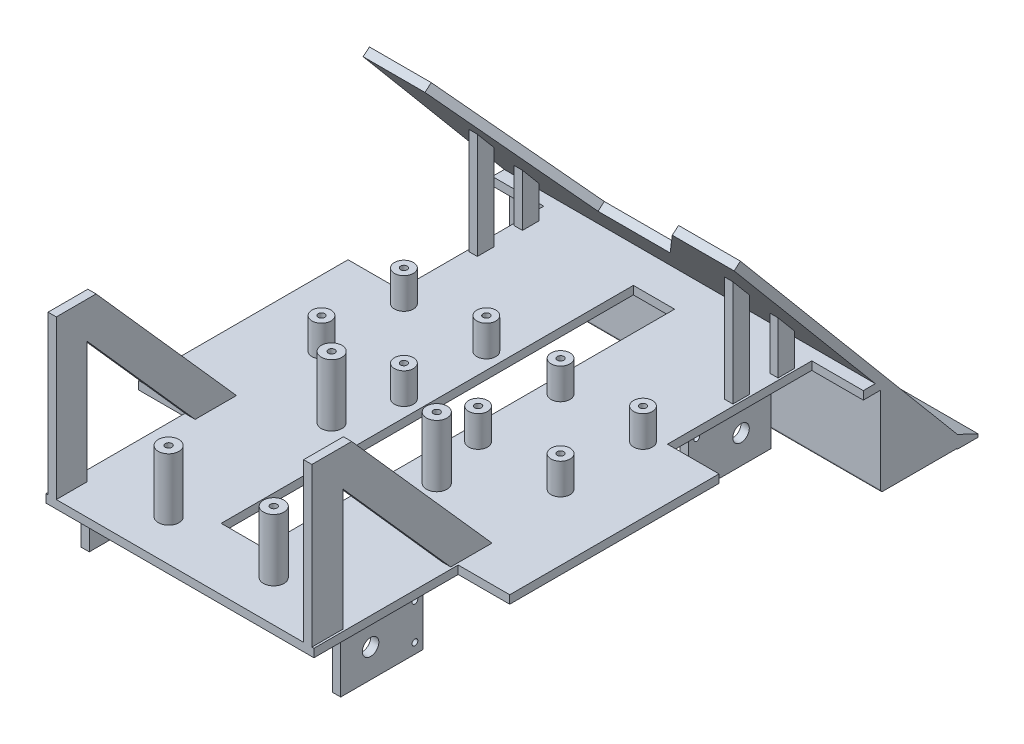
SolidWorks part; units mm, degrees
ref_plane "Front Plane" through (0, 0, 0) normal (0, 0, 1) x (1, 0, 0)
ref_plane "Top Plane" through (0, 0, 0) normal (0, 1, 0) x (1, 0, 0)
ref_plane "Right Plane" through (0, 0, 0) normal (1, 0, 0) x (0, 0, -1)
sketch "Sketch1" plane through (0, 0, 0) normal (0, 1, 0) x (1, 0, 0)
  line L1 (0, 0) -> (180, 0)
  line L2 (0, 0) -> (0, 250)
  line L3 (0, 250) -> (180, 250)
  line L4 (180, 0) -> (180, 250)
  line L5 (0, 0) -> (180, 250) construction
  line L6 (0, 250) -> (180, 0) construction
  point P4 (90, 125)
  dimension "D1" = 250
  dimension "D2" = 180
extrude "Boss-Extrude1" add sketch "Sketch1" along normal blind 4
ref_plane "Plane2" through (0, 124.7537, -148.6756) normal (0, 0.6428, -0.766) x (-1, 0, 0)
sketch "Sketch3" plane through (0, 124.7537, -148.6756) normal (0, 0.6428, -0.766) x (-1, 0, 0)
  line L0 (-180, 3.0642) -> (-180, -157.6327) construction
  line L1 (-180, -153.6185) -> (0, -153.6185)
  line L2 (-180, -153.6185) -> (-180, -160.6969)
  line L3 (-180, -160.6969) -> (0, -160.6969)
  line L4 (0, -153.6185) -> (0, -160.6969)
  line L5 (-180, -153.6185) -> (0, -160.6969) construction
  line L6 (-180, -160.6969) -> (0, -153.6185) construction
  point P4 (-90, -157.1577)
extrude "Cut-Extrude1" cut sketch "Sketch3" against normal blind 2
sketch "Sketch4" plane through (0, 123.4681, -147.1435) normal (0, 0.6428, -0.766) x (-1, 0, 0)
  line L0 (-180, 3.0642) -> (-180, -155.9545) construction
  line L1 (-180, -49.3572) -> (0, -49.3572)
  line L2 (-180, -49.3572) -> (-180, -217.9168)
  line L3 (-180, -217.9168) -> (0, -217.9168)
  line L4 (0, -49.3572) -> (0, -217.9168)
  line L5 (-180, -49.3572) -> (0, -217.9168) construction
  line L6 (-180, -217.9168) -> (0, -49.3572) construction
  point P4 (-90, -133.637)
extrude "Boss-Extrude3" add sketch "Sketch4" along normal blind 4
sketch "Sketch5" plane through (0, 0, 0) normal (-1, 0, 0) x (0, 0, 1)
  line L0 (-287.2178, -43.4659) -> (-287.2178, -37.243)
  line L1 (-290.2819, -40.8947) -> (-181.9339, 88.2294) construction
  line L2 (-287.2178, -37.243) -> (-290.2819, -40.8947)
  line L3 (-290.2819, -40.8947) -> (-287.2178, -43.4659)
extrude "Cut-Extrude2" cut sketch "Sketch5" against normal blind 214
sketch "Sketch6" plane through (0, 0, 0) normal (0, -1, 0) x (1, 0, 0)
  line L0 (0, -183.7456) -> (180, -183.7456) construction
  line L1 (0, -250) -> (0, 0) construction
  line L2 (180, 0) -> (180, -250) construction
  line L3 (0, -250.7456) -> (180, -250.7456) construction
  line L4 (0, -15) -> (180, -15) construction
  line L5 (27, -183.7456) -> (31, -183.7456)
  line L6 (27, -183.7456) -> (27, -223.7456)
  line L7 (27, -223.7456) -> (31, -223.7456)
  line L8 (31, -183.7456) -> (31, -223.7456)
  line L9 (27, -183.7456) -> (31, -223.7456) construction
  line L10 (27, -223.7456) -> (31, -183.7456) construction
  line L11 (0, 0) -> (180, 0) construction
  line L12 (90, -15) -> (90, -183.7456) construction
  line L13 (27, -15) -> (31, -15)
  line L14 (27, -15) -> (27, -55)
  line L15 (27, -55) -> (31, -55)
  line L16 (31, -15) -> (31, -55)
  line L17 (27, -15) -> (31, -55) construction
  line L18 (27, -55) -> (31, -15) construction
  line L19 (153, -223.7456) -> (149, -223.7456)
  line L20 (149, -183.7456) -> (149, -223.7456)
  line L21 (153, -183.7456) -> (149, -183.7456)
  line L22 (153, -183.7456) -> (153, -223.7456)
  line L23 (153, -55) -> (149, -55)
  line L24 (149, -15) -> (149, -55)
  line L25 (153, -15) -> (149, -15)
  line L26 (153, -15) -> (153, -55)
  point P12 (29, -203.7456)
  point P21 (29, -35)
  dimension "D1" = 67
  dimension "D2" = 4
  dimension "D3" = 27
  dimension "D4" = 40
  dimension "D5" = 15
  dimension "D6" = 4
  dimension "D7" = 40
  dimension "D8" = 27
extrude "Boss-Extrude4" add sketch "Sketch6" along normal blind 25
sketch "Sketch7" plane through (0, 126.0392, -150.2077) normal (0, 0.6428, -0.766) x (-1, 0, 0)
  line L0 (-90, -49.3572) -> (-90, -213.1498) construction
  line L1 (0, -49.3572) -> (-180, -49.3572) construction
  line L2 (-180, -213.1498) -> (0, -213.1498) construction
  line L3 (-180, -217.9168) -> (0, -217.9168) construction
  line L4 (-130, -167.9168) -> (-50, -167.9168)
  line L5 (-130, -167.9168) -> (-130, -217.9168)
  line L6 (-130, -217.9168) -> (-50, -217.9168)
  line L7 (-50, -167.9168) -> (-50, -217.9168)
  line L8 (-130, -167.9168) -> (-50, -217.9168) construction
  line L9 (-130, -217.9168) -> (-50, -167.9168) construction
  line L10 (-150, -49.3572) -> (-107.5, -113.8755)
  line L11 (-107.5, -113.8755) -> (-72.5, -113.8755)
  line L12 (-72.5, -113.8755) -> (-30, -49.3572)
  line L13 (-30, -49.3572) -> (-150, -49.3572)
  line L14 (-180, 3.0642) -> (-180, -155.9545) construction
  point P10 (-90, -192.9168)
  point P13 (-90, -167.9168)
  point P20 (-90, -113.8755)
  dimension "D1" = 80
  dimension "D2" = 50
  dimension "D3" = 30
  dimension "D4" = 35
extrude "Cut-Extrude3" cut sketch "Sketch7" against normal blind 5
sketch "Sketch8" plane through (27, 0, 0) normal (-1, 0, 0) x (0, 0, 1)
  line L0 (-187.7456, 0) -> (-187.7456, -25) construction
  line L1 (-183.7456, 0) -> (-223.7456, 0) construction
  line L2 (-183.7456, -25) -> (-223.7456, -25) construction
  line L3 (-183.7456, -25) -> (-183.7456, 0) construction
  line L4 (-51, 0) -> (-51, -25) construction
  line L5 (-15, 0) -> (-55, 0) construction
  line L6 (-15, -25) -> (-55, -25) construction
  line L7 (-55, -25) -> (-55, 0) construction
  circle A0 centre (-187.7456, -2.5) radius 1.4
  circle A1 centre (-187.7456, -20) radius 1.4
  circle A2 centre (-51, -2.5) radius 1.4
  circle A3 centre (-51, -20) radius 1.4
  dimension "D1" = 2.8
  dimension "D5" = 2.8
  dimension "D2" = 17.5
  dimension "D3" = 2.5
  dimension "D4" = 4
  dimension "D6" = 2.5
  dimension "D7" = 17.5
  dimension "D8" = 4
extrude "Cut-Extrude4" cut sketch "Sketch8" against normal blind 155
sketch "Sketch10" plane through (0, 0, -287.2178) normal (0, 0, -1) x (-1, 0, 0)
  line L1 (-180, -37.243) -> (-130, -37.243)
  line L2 (-180, -37.243) -> (-180, -43.4659)
  line L3 (-180, -43.4659) -> (-130, -43.4659)
  line L4 (-130, -37.243) -> (-130, -43.4659)
  line L5 (-180, -37.243) -> (-130, -43.4659) construction
  line L6 (-180, -43.4659) -> (-130, -37.243) construction
  line L7 (-50, -37.243) -> (0, -37.243)
  line L8 (-50, -37.243) -> (-50, -43.4659)
  line L9 (-50, -43.4659) -> (0, -43.4659)
  line L10 (0, -37.243) -> (0, -43.4659)
  line L11 (-50, -37.243) -> (0, -43.4659) construction
  line L12 (-50, -43.4659) -> (0, -37.243) construction
  point P4 (-155, -40.3544)
  point P11 (-25, -40.3544)
extrude "Boss-Extrude5" add sketch "Sketch10" along normal blind 10
sketch "Sketch11" plane through (0, 0, 0) normal (-1, 0, 0) x (0, 0, 1)
  line L0 (-297.2178, -41.9659) -> (-287.2178, -37.243)
  line L1 (-297.2178, -43.4659) -> (-297.2178, -37.243) construction
  line L2 (-297.2178, -37.243) -> (-287.2178, -37.243) construction
  line L3 (-297.2178, -43.4659) -> (-287.2178, -43.4659) construction
  line L4 (-297.2178, -41.9659) -> (-297.2178, -37.243)
  line L5 (-297.2178, -37.243) -> (-287.2178, -37.243)
  dimension "D1" = 1.5
extrude "Cut-Extrude5" cut sketch "Sketch11" against normal blind 199
sketch "Sketch12" plane through (0, 4, 0) normal (0, 1, 0) x (1, 0, 0)
  line L0 (90, 0) -> (90, 307.2534) construction
  line L1 (0, 0) -> (180, 0) construction
  line L3 (80, 230) -> (100, 230)
  line L4 (80, 230) -> (80, 30)
  line L5 (80, 30) -> (100, 30)
  line L6 (100, 230) -> (100, 30)
  line L7 (80, 230) -> (100, 30) construction
  line L8 (80, 30) -> (100, 230) construction
  point P8 (90, 130)
  point P9 (90, 230)
  dimension "D1" = 20
  dimension "D2" = 30
  dimension "D3" = 200
extrude "Cut-Extrude6" cut sketch "Sketch12" against normal blind 5
sketch "Sketch13" plane through (0, 4, 0) normal (0, 1, 0) x (1, 0, 0)
  line L0 (0, 0) -> (180, 0) construction
  line L1 (64.5, 99.1) -> (115.5, 99.1) construction
  line L2 (64.5, 99.1) -> (64.5, 20) construction
  line L3 (64.5, 20) -> (115.5, 20) construction
  line L4 (115.5, 99.1) -> (115.5, 20) construction
  circle A0 centre (115.5, 99.1) radius 1.6
  circle A1 centre (64.5, 99.1) radius 1.6
  circle A2 centre (64.5, 20) radius 1.6
  circle A3 centre (115.5, 20) radius 1.6
  circle A4 centre (64.5, 99.1) radius 5
  circle A5 centre (115.5, 99.1) radius 5
  circle A6 centre (115.5, 20) radius 5
  circle A7 centre (64.5, 20) radius 5
  point P4 (87.5576, 87.4411)
  point P7 (90, 0)
  point P8 (90, 20)
  dimension "D3" = 3.2
  dimension "D4" = 10
  dimension "D5" = 20
  dimension "D1" = 79.1
  dimension "D2" = 51
extrude "Boss-Extrude6" add sketch "Sketch13" along normal blind 30
sketch "Sketch14" plane through (0, 4, 0) normal (0, 1, 0) x (1, 0, 0)
  line L0 (0, 146.6712) -> (80, 146.6712) construction
  line L1 (32, 166.6712) -> (72, 166.6712) construction
  line L2 (32, 166.6712) -> (32, 126.6712) construction
  line L3 (32, 126.6712) -> (72, 126.6712) construction
  line L4 (72, 166.6712) -> (72, 126.6712) construction
  line L5 (32, 166.6712) -> (72, 126.6712) construction
  line L6 (32, 126.6712) -> (72, 166.6712) construction
  line L7 (108, 166.6712) -> (148, 166.6712) construction
  line L8 (108, 166.6712) -> (108, 126.6712) construction
  line L9 (108, 126.6712) -> (148, 126.6712) construction
  line L10 (148, 166.6712) -> (148, 126.6712) construction
  line L11 (108, 166.6712) -> (148, 126.6712) construction
  line L12 (108, 126.6712) -> (148, 166.6712) construction
  line L13 (0, 247.3892) -> (0, 0) construction
  line L14 (80, 230) -> (80, 30) construction
  line L15 (100, 146.6712) -> (180, 146.6712) construction
  line L16 (100, 30) -> (100, 230) construction
  line L17 (180, 0) -> (180, 247.3892) construction
  line L18 (50, 287.2178) -> (0, 287.2178) construction
  circle A0 centre (32, 166.6712) radius 1.6
  circle A1 centre (72, 166.6712) radius 1.6
  circle A2 centre (32, 126.6712) radius 1.6
  circle A3 centre (72, 126.6712) radius 1.6
  circle A4 centre (108, 166.6712) radius 1.6
  circle A5 centre (148, 166.6712) radius 1.6
  circle A6 centre (108, 126.6712) radius 1.6
  circle A7 centre (148, 126.6712) radius 1.6
  circle A8 centre (32, 166.6712) radius 4.6
  circle A9 centre (72, 166.6712) radius 4.6
  circle A10 centre (72, 126.6712) radius 4.6
  circle A11 centre (32, 126.6712) radius 4.6
  circle A12 centre (108, 166.6712) radius 4.6
  circle A13 centre (148, 166.6712) radius 4.6
  circle A14 centre (148, 126.6712) radius 4.6
  circle A15 centre (108, 126.6712) radius 4.6
  point P4 (40, 146.6712)
  point P9 (140, 146.6712)
  point P24 (40, 146.6712)
  point P26 (140, 146.6712)
  point P42 (128, 146.6712)
  point P43 (52, 146.6712)
  dimension "D2" = 3.2
  dimension "D4" = 3
  dimension "D1" = 40
  dimension "D3" = 120.5466
  dimension "D5" = 8
  dimension "D6" = 8
extrude "Boss-Extrude7" add sketch "Sketch14" along normal blind 15
ref_plane "Plane3" through (30, 0, 0) normal (-1, 0, 0) x (0, 0, 1)
sketch "Sketch15" plane through (30, 0, 0) normal (-1, 0, 0) x (0, 0, 1)
  line L0 (0, 4) -> (0, 80.7504)
  line L1 (-15, 4) -> (-15, 63)
  line L2 (-247.3892, 4) -> (0, 4) construction
  line L3 (-19.3019, 80.7504) -> (-87.4193, 4)
  line L4 (-15, 63) -> (-67.3636, 4)
  line L5 (-15, 4) -> (0, 4)
  line L6 (-87.4193, 4) -> (-67.3636, 4)
  line L7 (-19.3019, 80.7504) -> (0, 80.7504)
  dimension "D2" = 15
  dimension "D3" = 15
extrude "Boss-Extrude8" add sketch "Sketch15" along normal blind 4
ref_plane "Plane4" through (90, 0, 0) normal (1, 0, 0) x (0, 0, -1)
mirror "Mirror1" about plane through (90, 0, 0) normal (1, 0, 0) of "Boss-Extrude8"
sketch "Sketch16" plane through (30, 0, 0) normal (-1, 0, 0) x (0, 0, 1)
  line L0 (-212.2711, 45.8521) -> (-212.2711, 4)
  line L1 (-247.3892, 4) -> (-178.8698, 85.6583) construction
  line L2 (-247.3892, 4) -> (0, 4) construction
  line L3 (-212.2711, 4) -> (-204.2711, 4)
  line L4 (-204.2711, 4) -> (-204.2711, 55.3862)
  line L5 (-204.2711, 55.3862) -> (-212.2711, 45.8521)
  line L6 (-234.1848, 19.7364) -> (-234.1848, 4)
  line L7 (-234.1848, 4) -> (-226.1848, 4)
  line L8 (-226.1848, 4) -> (-226.1848, 29.2704)
  line L9 (-226.1848, 29.2704) -> (-234.1848, 19.7364)
  dimension "D1" = 8
  dimension "D2" = 8
extrude "Boss-Extrude9" add sketch "Sketch16" along normal blind 4
mirror "Mirror2" about plane through (90, 0, 0) normal (1, 0, 0) of "Boss-Extrude9"
sketch "Sketch17" plane through (0, 4, 0) normal (0, 1, 0) x (1, 0, 0)
  line L0 (0, 247.3892) -> (0, 0) construction
  line L1 (0, 70) -> (25, 70)
  line L2 (0, 70) -> (0, 0)
  line L3 (0, 0) -> (25, 0)
  line L4 (25, 70) -> (25, 0)
  line L5 (0, 70) -> (25, 0) construction
  line L6 (0, 0) -> (25, 70) construction
  line L7 (0, 0) -> (26, 0) construction
  line L8 (0, 287.2178) -> (0, 181.9339) construction
  line L9 (0, 241.5539) -> (25, 241.5539)
  line L10 (0, 241.5539) -> (0, 171.5539)
  line L11 (0, 171.5539) -> (25, 171.5539)
  line L12 (25, 241.5539) -> (25, 171.5539)
  line L13 (0, 241.5539) -> (25, 171.5539) construction
  line L14 (0, 171.5539) -> (25, 241.5539) construction
  point P4 (12.5, 35)
  point P13 (12.5, 206.5539)
  dimension "D1" = 25
  dimension "D2" = 70
  dimension "D3" = 25
  dimension "D4" = 70
extrude "Cut-Extrude8" cut sketch "Sketch17" against normal blind 19 contours L2 L3 L4 L1 | L10 L9 L12 L11
sketch "Sketch18" plane through (27, 0, 0) normal (-1, 0, 0) x (0, 0, 1)
  line L0 (-55, -12.5) -> (-15, -12.5) construction
  line L3 (-51, -2.5) -> (-51, -20) construction
  line L5 (-15, 0) -> (-55, 0) construction
  line L6 (-223.7456, -11.2) -> (-183.7456, -11.2) construction
  line L7 (-223.7456, -25) -> (-223.7456, 0) construction
  line L8 (-183.7456, -25) -> (-183.7456, 0) construction
  line L10 (-187.7456, -2.5) -> (-187.7456, -20) construction
  circle A0 centre (-29.5, -11.2) radius 4
  circle A2 centre (-209.2456, -11.2) radius 4
  dimension "D2" = 8
  dimension "D4" = 8
  dimension "D1" = 21.5
  dimension "D3" = 11.2
  dimension "D5" = 21.5
extrude "Cut-Extrude9" cut sketch "Sketch18" against normal blind 145
mirror "Mirror3" about plane through (90, 0, 0) normal (1, 0, 0) of "Cut-Extrude8"
sketch "Sketch19" plane through (0, 0, 0) normal (-1, 0, 0) x (0, 0, 1)
  line L0 (-250, 0.8886) -> (-250, -43.0527)
  line L1 (-250, -43.0527) -> (-287.7102, -43.0527)
  line L3 (-252.9065, -2.5753) -> (-252.9065, -40.0527)
  line L4 (-287.2178, -43.4659) -> (-250, 0.8886) construction
  line L5 (-252.9065, -40.0527) -> (-284.3538, -40.0527)
  line L6 (-284.3538, -40.0527) -> (-287.7102, -43.0527)
  line L7 (-252.9065, -2.5753) -> (-250, 0.8886)
  line L8 (-287.2178, -43.4659) -> (-250, 0.8886) construction
  line L9 (-250, 0.8886) -> (-250, 0) construction
  dimension "D1" = 2.9065
  dimension "D2" = 3
extrude "Boss-Extrude10" add sketch "Sketch19" against normal blind 180 separate body
sketch "Sketch23" plane through (50, 0, 0) normal (1, 0, 0) x (0, 0, -1)
  line L0 (250, 0.8886) -> (287.7102, -43.0527)
  line L1 (287.7102, -43.0527) -> (250, -43.0527)
  line L2 (250, -43.0527) -> (250, 0.8886)
sketch "Sketch27" plane through (0, 123.4681, -147.1435) normal (0, 0.6428, -0.766) x (-1, 0, 0)
  line L0 (-180, -164.5379) -> (0, -164.5379) construction
  line L1 (-130, -167.9168) -> (-50, -167.9168)
  line L2 (-130, -167.9168) -> (-130, -164.5379)
  line L3 (-130, -164.5379) -> (-50, -164.5379)
  line L4 (-50, -167.9168) -> (-50, -164.5379)
  line L5 (-130, -167.9168) -> (-50, -164.5379) construction
  line L6 (-130, -164.5379) -> (-50, -167.9168) construction
  line L7 (-50, -213.1498) -> (-50, -167.9168) construction
  point P4 (-90, -166.2274)
extrude "Boss-Extrude17" add sketch "Sketch27" along normal blind 3
extrude "Boss-Extrude13" add sketch "Sketch23" against normal blind 3
sketch "Sketch24" plane through (130, 0, 0) normal (-1, 0, 0) x (0, 0, 1)
  line L0 (-252.9065, -2.5753) -> (-252.9065, -40.0527)
  line L1 (-252.9065, -40.0527) -> (-284.3538, -40.0527)
  line L2 (-284.3538, -40.0527) -> (-252.9065, -2.5753)
extrude "Boss-Extrude14" add sketch "Sketch24" against normal blind 3
sketch "Sketch25" plane through (0, 0, 0) normal (-1, 0, 0) x (0, 0, 1)
  line L0 (-252.9065, -2.5753) -> (-252.9065, -40.0527)
  line L1 (-252.9065, -40.0527) -> (-284.3538, -40.0527)
  line L2 (-284.3538, -40.0527) -> (-252.9065, -2.5753)
extrude "Boss-Extrude15" add sketch "Sketch25" against normal blind 3
sketch "Sketch26" plane through (180, 0, 0) normal (1, 0, 0) x (0, 0, -1)
  line L0 (252.9065, -2.5753) -> (252.9065, -40.0527)
  line L1 (252.9065, -40.0527) -> (284.3538, -40.0527)
  line L2 (284.3538, -40.0527) -> (252.9065, -2.5753)
extrude "Boss-Extrude16" add sketch "Sketch26" against normal blind 3
fillet "Fillet1" radius 1 1 edges at (90, -43.0527, -250)
sketch "Sketch28" plane through (0, -40.0527, 0) normal (0, 1, 0) x (1, 0, 0)
  line L0 (130, 258.1426) -> (130, 287.2178) construction
  line L1 (50, 287.2178) -> (130, 287.2178)
  line L2 (50, 287.2178) -> (50, 252.9065)
  line L3 (50, 252.9065) -> (130, 252.9065)
  line L4 (130, 287.2178) -> (130, 252.9065)
  line L5 (50, 287.2178) -> (130, 252.9065) construction
  line L6 (50, 252.9065) -> (130, 287.2178) construction
  line L7 (130, 284.3538) -> (130, 252.9065) construction
  point P4 (90, 270.0621)
extrude "Cut-Extrude14" cut sketch "Sketch28" against normal blind 3
